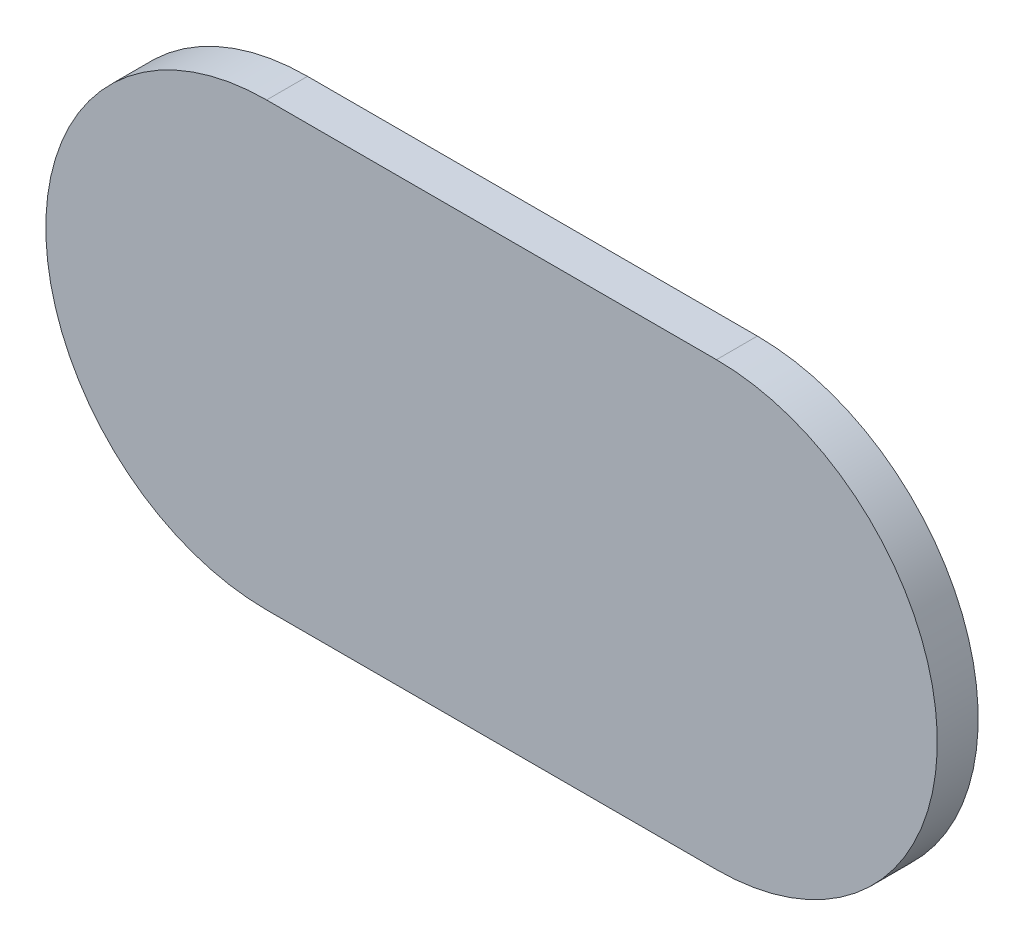
SolidWorks part; units mm, degrees
material "Acrylique (impact moyen-haut)"
ref_plane "Plan de face" through (0, 0, 0) normal (0, 0, 1) x (1, 0, 0)
ref_plane "Plan de dessus" through (0, 0, 0) normal (0, 1, 0) x (1, 0, 0)
ref_plane "Plan de droite" through (0, 0, 0) normal (1, 0, 0) x (0, 0, -1)
sketch "Esquisse1" plane through (0, 0, 0) normal (0, 0, 1) x (1, 0, 0)
  line L0 (2.75, 0) -> (-2.75, 0) construction
  line L1 (2.75, -2.7) -> (-2.75, -2.7)
  line L2 (2.75, 2.7) -> (-2.75, 2.7)
  arc A1 (2.75, -2.7) -> (2.75, 2.7) centre (2.75, 0) ccw
  arc A2 (-2.75, 2.7) -> (-2.75, -2.7) centre (-2.75, 0) ccw
  point P3 (0, 0)
  dimension "D1" = 5.4
  dimension "D2" = 5.5
extrude "Boss.-Extru.1" add sketch "Esquisse1" along normal blind 0.5
